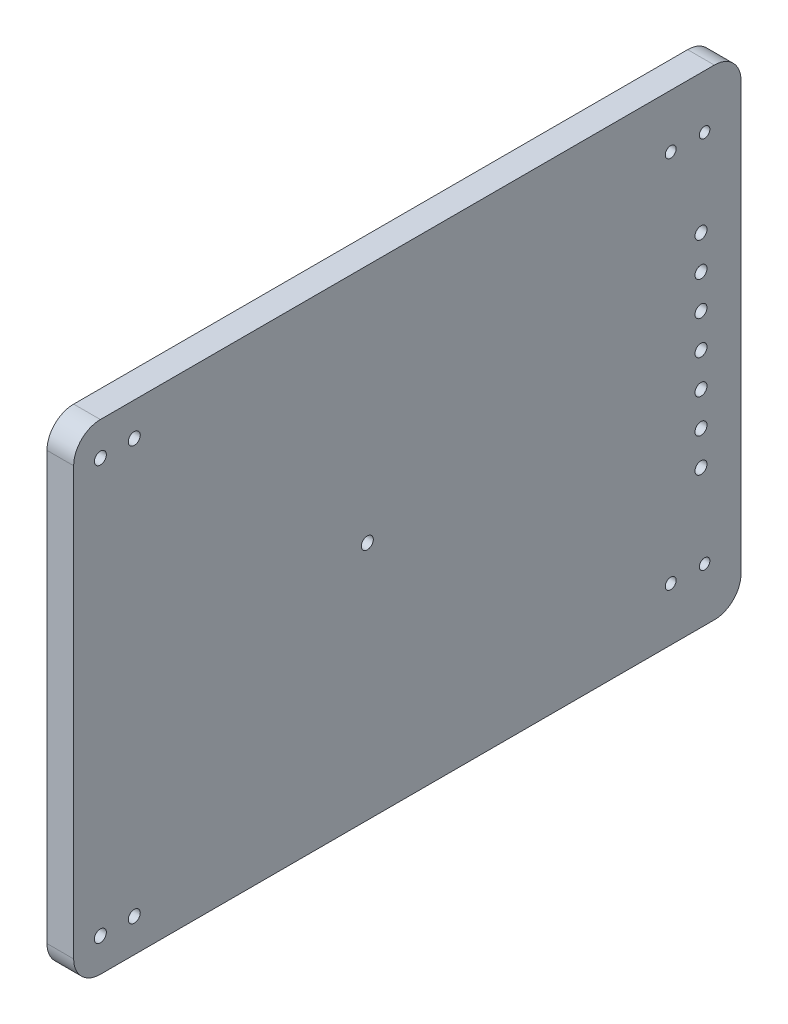
SolidWorks part; units mm, degrees
material "45"
ref_plane "前视基准面" through (0, 0, 0) normal (0, 0, 1) x (1, 0, 0)
ref_plane "上视基准面" through (0, 0, 0) normal (0, 1, 0) x (1, 0, 0)
ref_plane "右视基准面" through (0, 0, 0) normal (1, 0, 0) x (0, 0, -1)
sketch "草图1" plane through (0, 0, 0) normal (1, 0, 0) x (0, 0, -1)
  line L1 (-23, 18) -> (23, 18)
  line L2 (-25, 16) -> (-25, -16)
  line L3 (-23, -18) -> (23, -18)
  line L4 (25, 16) -> (25, -16)
  line L5 (-25, 18) -> (25, -18) construction
  line L6 (-25, -18) -> (25, 18) construction
  arc A0 (23, 18) -> (25, 16) centre (23, 16) cw
  arc A1 (23, -18) -> (25, -16) centre (23, -16) ccw
  arc A2 (-25, -16) -> (-23, -18) centre (-23, -16) ccw
  arc A3 (-23, 18) -> (-25, 16) centre (-23, 16) ccw
  point P0 (0, 0)
  dimension "D3" = 2
  dimension "D1" = 50
  dimension "D2" = 36
extrude "凸台-拉伸1" add sketch "草图1" along normal mid plane 2
sketch "草图2" plane through (1, 0, 0) normal (1, 0, 0) x (0, 0, -1)
  line L0 (23, 18) -> (-23, 18) construction
  line L1 (-25, 16) -> (-25, -16) construction
  circle A0 centre (-23, 15.5) radius 0.45
  circle A1 centre (-20.46, 15.5) radius 0.45
  dimension "D1" = 0.9
  dimension "D2" = 0.9
  dimension "D3" = 2.54
  dimension "D4" = 2.5
  dimension "D5" = 2
extrude "切除-拉伸1" cut sketch "草图2" against normal blind 2
mirror "镜向1" about plane through (0, 0, 0) normal (0, 1, 0) of "切除-拉伸1"
sketch "草图3" plane through (1, 0, 0) normal (1, 0, 0) x (0, 0, -1)
  line L1 (25, -16) -> (25, 16) construction
  circle A0 centre (22, 7.62) radius 0.45
  dimension "D1" = 0.9
  dimension "D2" = 3
  dimension "D3" = 7.62
extrude "切除-拉伸2" cut sketch "草图3" against normal blind 2
pattern_linear "阵列(线性)1" count 7 spacing 2.54 along (0, -1, 0) of "切除-拉伸2"
sketch "草图4" plane through (1, 0, 0) normal (1, 0, 0) x (0, 0, -1)
  line L1 (-25, 16) -> (-25, -16) construction
  circle A0 centre (-3, 0) radius 0.45
  dimension "D2" = 0.9
  dimension "D1" = 22
extrude "切除-拉伸3" cut sketch "草图4" against normal blind 2
sketch "草图5" plane through (1, 0, 0) normal (1, 0, 0) x (0, 0, -1)
  line L0 (23, 18) -> (-23, 18) construction
  line L1 (25, -16) -> (25, 16) construction
  circle A0 centre (22.27, 14) radius 0.3949
  circle A1 centre (19.73, 14) radius 0.4082
  dimension "D1" = 2.54
  dimension "D2" = 4
  dimension "D3" = 2.73
extrude "切除-拉伸4" cut sketch "草图5" against normal blind 2
mirror "镜向2" about plane through (0, 0, 0) normal (0, 1, 0) of "切除-拉伸4"
